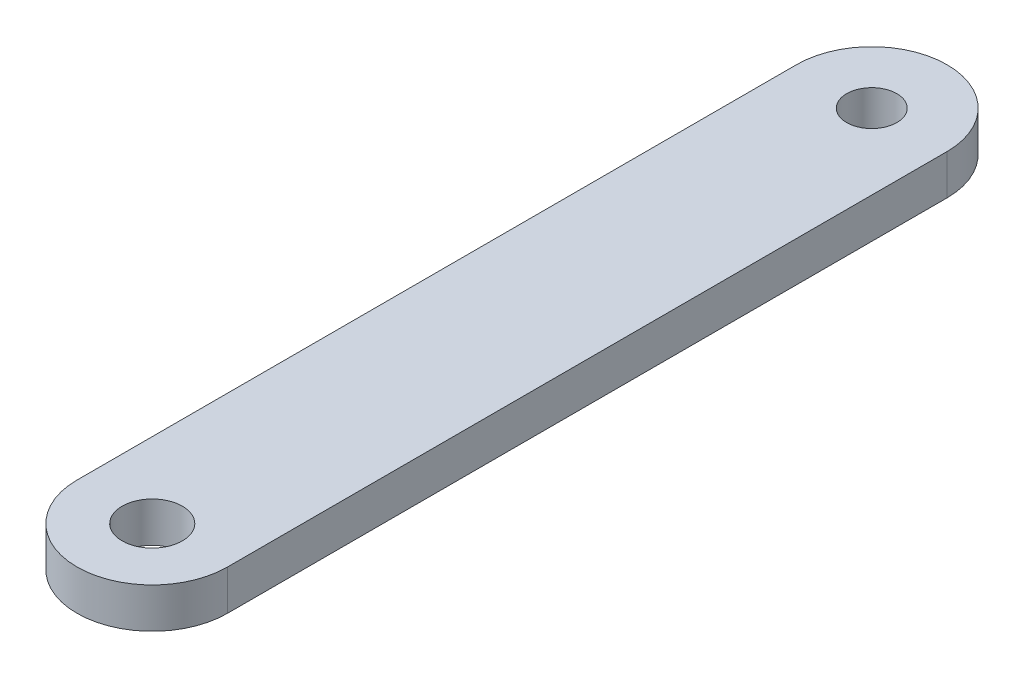
SolidWorks part; units mm, degrees
ref_plane "Front Plane" through (0, 0, 0) normal (0, 0, 1) x (1, 0, 0)
ref_plane "Top Plane" through (0, 0, 0) normal (0, 1, 0) x (1, 0, 0)
ref_plane "Right Plane" through (0, 0, 0) normal (1, 0, 0) x (0, 0, -1)
sketch "Sketch1" plane through (0, 0, 0) normal (0, 1, 0) x (1, 0, 0)
  line L0 (1.2912, -4.823) -> (1.2912, 31.027) construction
  line L1 (-2.4588, -4.823) -> (-2.4588, 31.027)
  line L2 (5.0412, 31.027) -> (5.0412, -4.823)
  circle A0 centre (1.2912, 31.027) radius 1.25
  circle A1 centre (1.2912, -4.823) radius 1.5
  arc A2 (5.0412, 31.027) -> (-2.4588, 31.027) centre (1.2912, 31.027) ccw
  arc A3 (-2.4588, -4.823) -> (5.0412, -4.823) centre (1.2912, -4.823) ccw
  dimension "D2" = 2.5
  dimension "D3" = 3
  dimension "D4" = 7.5
  dimension "D1" = 35.85
extrude "Boss-Extrude1" add sketch "Sketch1" along normal blind 2
